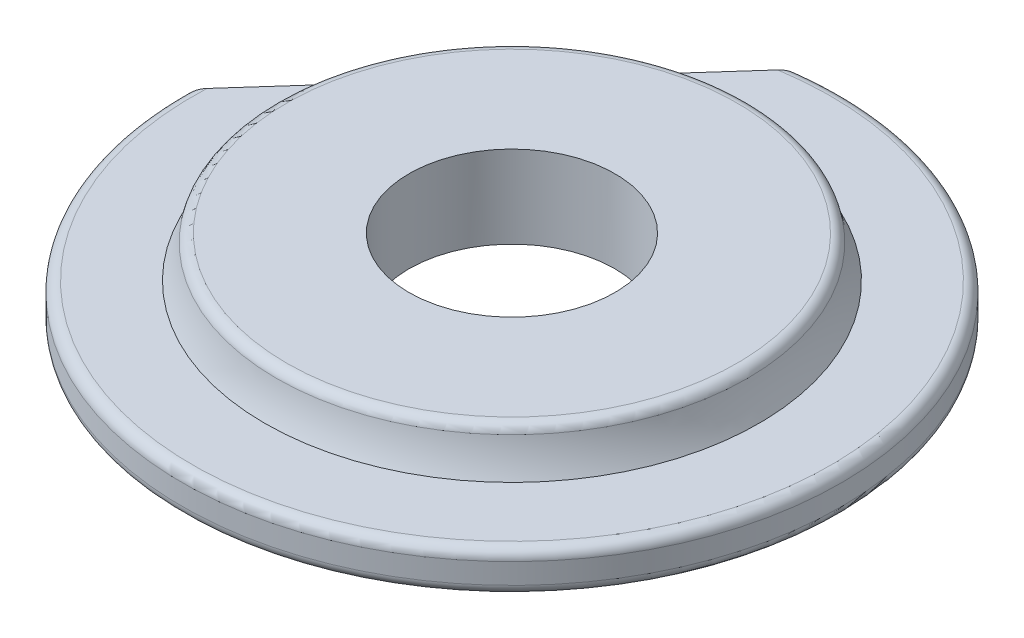
SolidWorks part; units mm, degrees
ref_plane "Plan de face" through (0, 0, 0) normal (0, 0, 1) x (1, 0, 0)
ref_plane "Plan de dessus" through (0, 0, 0) normal (0, 1, 0) x (1, 0, 0)
ref_plane "Plan de droite" through (0, 0, 0) normal (1, 0, 0) x (0, 0, -1)
sketch "Esquisse1" plane through (0, 0, 0) normal (0, 0, 1) x (1, 0, 0)
  line L0 (0, 0) -> (80, 0)
  line L1 (23.2031, 20) -> (80, 20)
  line L2 (0, 0) -> (0, 10)
  line L3 (0, 10) -> (20, 10)
  line L4 (80, 20) -> (80, 0)
  line L5 (80, 20) -> (80, -86.1718) construction
  arc A1 (20, 10) -> (23.2031, 20) centre (-7.0047, 24.1629) ccw
  dimension "D1" = 20
  dimension "D2" = 10
  dimension "D3" = 20
  dimension "D4" = 80
revolve "Révolution1" add sketch "Esquisse1" angle 360 about L4
fillet "Congé1" radius 2.5 3 edges at (80, 20, 56.7969) (80, 0, 80) (80, 10, 80)
sketch "Esquisse3" plane through (0, 10, 0) normal (0, 1, 0) x (1, 0, 0)
  line L0 (0.0017, 0.5216) -> (70.5177, 79.436)
  arc A0 (0.0017, 0.5216) -> (70.5177, 79.436) centre (80, 0) cw
  circle A1 centre (80, 0) radius 80 construction
extrude "Enlèv. mat.-Extru.1" cut sketch "Esquisse3" against normal up to next
sketch "Esquisse4" plane through (0, 20, 0) normal (0, 1, 0) x (1, 0, 0)
  circle A0 centre (80, 0) radius 25
  dimension "D1" = 50
extrude "Enlèv. mat.-Extru.2" cut sketch "Esquisse4" against normal up to next
scale "Echelle1" scale about centroid uniform scaling yes scale factor 0.25
